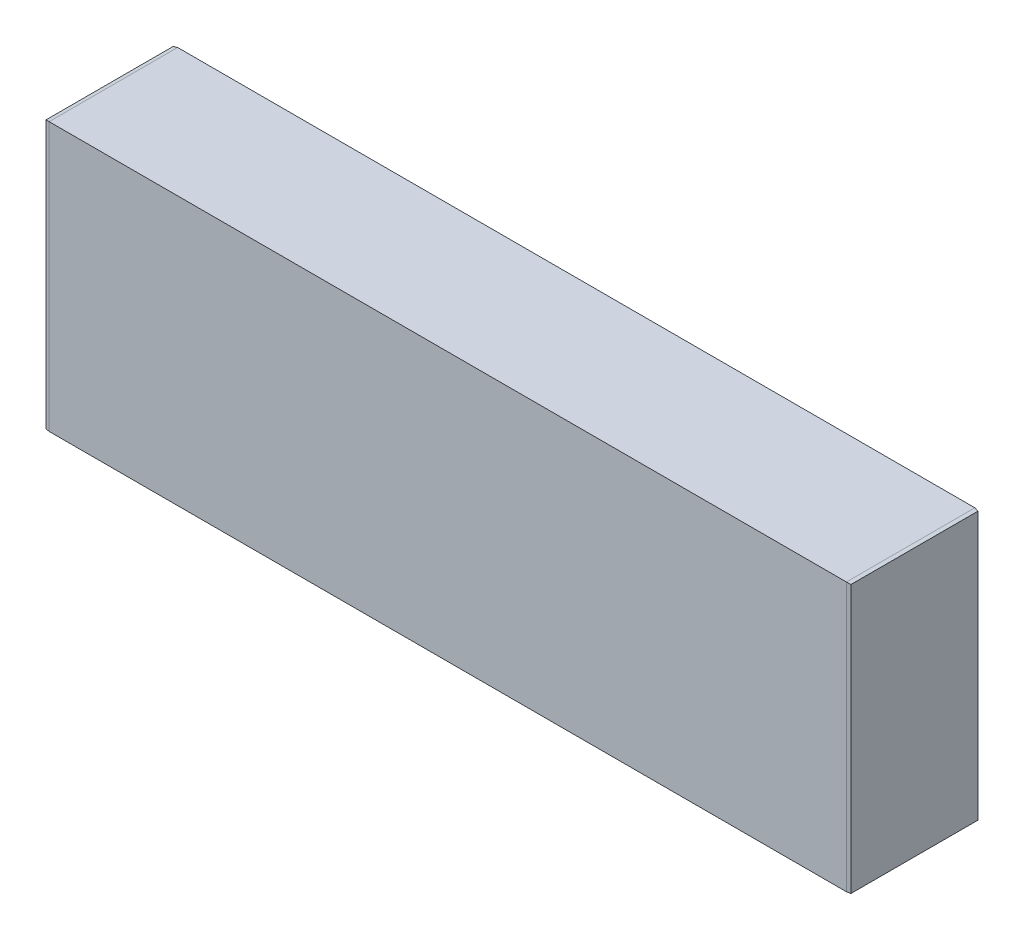
SolidWorks part; units mm, degrees
ref_plane "Front Plane" through (0, 0, 0) normal (0, 0, 1) x (1, 0, 0)
ref_plane "Top Plane" through (0, 0, 0) normal (0, 1, 0) x (1, 0, 0)
ref_plane "Right Plane" through (0, 0, 0) normal (1, 0, 0) x (0, 0, -1)
sketch "Sketch1" plane through (0, 0, 0) normal (0, 0, 1) x (1, 0, 0)
  line L1 (-45.3301, 26.9451) -> (167.6699, 26.9451)
  line L2 (-45.3301, 26.9451) -> (-45.3301, -44.0549)
  line L3 (-45.3301, -44.0549) -> (167.6699, -44.0549)
  line L4 (167.6699, 26.9451) -> (167.6699, -44.0549)
  dimension "D1" = 213
  dimension "D2" = 71
extrude "Boss-Extrude1" add sketch "Sketch1" along normal blind 34
chamfer "Chamfer1" distance 1 angle 10 3 edges at (-45.3301, -8.5549, 34) (-45.3301, -8.5549, 0) (-45.3301, 26.9451, 17)
chamfer "Chamfer2" distance 1 angle 10 3 edges at (167.6699, -8.5549, 0) (167.6699, -8.5549, 34) (167.6699, 26.9451, 17)
sketch "Sketch3" plane through (-45.3301, 0, 0) normal (-1, 0, 0) x (0, 0, 1)
  line L0 (18.2561, -14.9433) -> (18.2561, -35.97) construction
  line L1 (5.1763, -17.6597) -> (28.8237, -17.6597)
  line L2 (5.1763, -17.6597) -> (5.1763, -33.8573)
  line L3 (5.1763, -33.8573) -> (28.8237, -33.8573)
  line L4 (28.8237, -17.6597) -> (28.8237, -33.8573)
  line L5 (6.7058, -19.1688) -> (10.7058, -19.1688)
  line L6 (6.7058, -19.1688) -> (6.7058, -32.5494)
  line L7 (6.7058, -32.5494) -> (10.7058, -32.5494)
  line L8 (10.7058, -19.1688) -> (10.7058, -32.5494)
  line L9 (12.2353, -19.1688) -> (16.2353, -19.1688)
  line L10 (12.2353, -19.1688) -> (12.2353, -32.5609)
  line L11 (12.2353, -32.5609) -> (16.2353, -32.5609)
  line L12 (16.2353, -19.1688) -> (16.2353, -32.5609)
  line L13 (17.7647, -19.1688) -> (21.7647, -19.1688)
  line L14 (17.7647, -19.1688) -> (17.7647, -32.5803)
  line L15 (17.7647, -32.5803) -> (21.7647, -32.5803)
  line L16 (21.7647, -19.1688) -> (21.7647, -32.5803)
  line L17 (23.2942, -19.1688) -> (27.2942, -19.1688)
  line L18 (23.2942, -19.1688) -> (23.2942, -32.6081)
  line L19 (23.2942, -32.6081) -> (27.2942, -32.6081)
  line L20 (27.2942, -19.1688) -> (27.2942, -32.6081)
  line L21 (5.1763, -19.1688) -> (6.7058, -19.1688) construction
  line L22 (10.7058, -19.1688) -> (12.2353, -19.1688) construction
  line L23 (16.2353, -19.1688) -> (17.7647, -19.1688) construction
  line L24 (21.7647, -19.1688) -> (23.2942, -19.1688) construction
  line L25 (27.2942, -19.1688) -> (28.8237, -19.1688) construction
  line L26 (33.8237, -44.0549) -> (33.8237, 26.7688) construction
  line L27 (0.1763, 26.7688) -> (0.1763, -44.0549) construction
  line L28 (33.8237, -44.0549) -> (0.1763, -44.0549) construction
  line L29 (10.7058, -32.5494) -> (10.8058, -33.8573) construction
  line L30 (16.2353, -32.5609) -> (16.4353, -33.8573) construction
  line L31 (21.7647, -32.5803) -> (22.0647, -33.8573) construction
  line L32 (27.2942, -32.6081) -> (27.6942, -33.8573) construction
  dimension "D1" = 4
  dimension "D2" = 4
  dimension "D3" = 4
  dimension "D4" = 4
  dimension "D5" = 5
  dimension "D6" = 5
  dimension "D7" = 10.1976
extrude "Cut-Extrude2" cut sketch "Sketch3" against normal blind 1
sketch "Sketch4" plane through (-45.3301, 0, 0) normal (-1, 0, 0) x (0, 0, 1)
  line L0 (8.6763, -39.3573) -> (8.6763, -41.974) construction
  line L1 (8.1763, -35.8573) -> (9.1763, -35.8573)
  line L2 (8.1763, -35.8573) -> (8.1763, -38.3573)
  line L3 (8.1763, -41.8573) -> (9.1763, -41.8573)
  line L4 (9.1763, -35.8573) -> (9.1763, -38.3573)
  line L5 (5.6763, -38.3573) -> (8.1763, -38.3573)
  line L6 (5.6763, -38.3573) -> (5.6763, -39.3573)
  line L7 (5.6763, -39.3573) -> (8.1763, -39.3573)
  line L8 (11.6763, -38.3573) -> (11.6763, -39.3573)
  line L9 (8.954, -38.8573) -> (13.6707, -38.8573) construction
  line L10 (5.1763, -33.8573) -> (28.8237, -33.8573) construction
  line L11 (0.1763, 26.7688) -> (0.1763, -44.0549) construction
  line L12 (13.6707, -38.8573) -> (32.3354, -38.8573) construction
  line L13 (22.7204, -38.3573) -> (28.7204, -38.3573)
  line L14 (22.7204, -38.3573) -> (22.7204, -39.3573)
  line L15 (22.7204, -39.3573) -> (28.7204, -39.3573)
  line L16 (28.7204, -38.3573) -> (28.7204, -39.3573)
  line L17 (9.1763, -38.3573) -> (11.6763, -38.3573)
  line L18 (8.1763, -39.3573) -> (8.1763, -41.8573)
  line L19 (9.1763, -39.3573) -> (11.6763, -39.3573)
  line L20 (9.1763, -39.3573) -> (9.1763, -41.8573)
  dimension "D1" = 1
  dimension "D2" = 1
  dimension "D3" = 6
  dimension "D5" = 6
  dimension "D6" = 3
  dimension "D7" = 2
  dimension "D8" = 5.5
  dimension "D9" = 6
  dimension "D10" = 1
  dimension "D11" = 0.5
extrude "Cut-Extrude3" cut sketch "Sketch4" against normal blind 1
